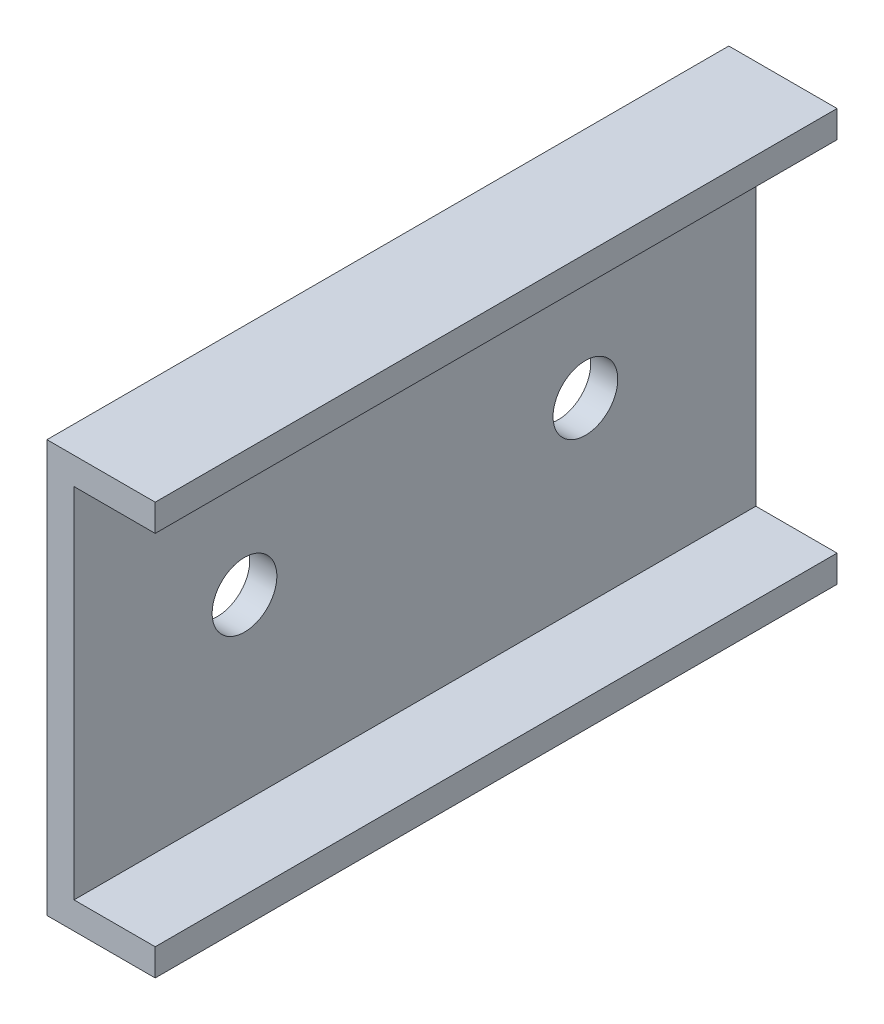
SolidWorks part; units mm, degrees
ref_plane "Front Plane" through (0, 0, 0) normal (0, 0, 1) x (1, 0, 0)
ref_plane "Top Plane" through (0, 0, 0) normal (0, 1, 0) x (1, 0, 0)
ref_plane "Right Plane" through (0, 0, 0) normal (1, 0, 0) x (0, 0, -1)
sketch "Sketch1" plane through (0, 0, 0) normal (0, 0, 1) x (1, 0, 0)
  line L0 (0, 0) -> (6.35, 0)
  line L1 (0, 0) -> (0, 24.175)
  line L2 (0, 24.175) -> (6.35, 24.175)
  line L3 (1.5875, 1.5875) -> (6.35, 1.5875)
  line L4 (1.5875, 1.5875) -> (1.5875, 22.5875)
  line L5 (1.5875, 22.5875) -> (6.35, 22.5875)
  line L6 (6.35, 22.5875) -> (6.35, 24.175)
  line L7 (6.35, 1.5875) -> (6.35, 0)
  dimension "D1" = 21
  dimension "D2" = 6.35
  dimension "D3" = 1.5875
extrude "Boss-Extrude1" add sketch "Sketch1" along normal blind 20
hole_wizard "#6 Clearance Hole1" positions "Sketch5" profile "Sketch6" hole size "#6" standard "ANSI Inch"
sketch "Sketch5" plane through (0, 0, 0) normal (-1, 0, 0) x (0, 0, 1)
  line L2 (20, 24.175) -> (20, 0) construction
  line L4 (0, 12.0875) -> (20, 12.0875) construction
  line L5 (0, 24.175) -> (0, 0) construction
  point P0 (10, 12.0875)
  dimension "D1" = 10
sketch "Sketch6" plane through (0, 12.0875, 10) normal (0, 1, 0) x (0, 0, 1)
  line L0 (0, 0) -> (0, 2.7273)
  line L1 (0, 2.7273) -> (1.8986, 1.5865)
  line L2 (1.8986, 1.5865) -> (1.8986, 0)
  line L5 (1.8986, 0) -> (0, 0)
  line L10 (0, 2.7273) -> (-1.8987, 1.5865) construction
  line L11 (0, -6.35) -> (0, 107.95) construction
  dimension "Hole Dia." = 3.7973
  dimension "Hole Depth" = 1.5865
  dimension "Drill Angle" = 118
mirror "Mirror1" about plane through (0, 0, 0) normal (0, 0, -1) of "#6 Clearance Hole1", "Boss-Extrude1"
